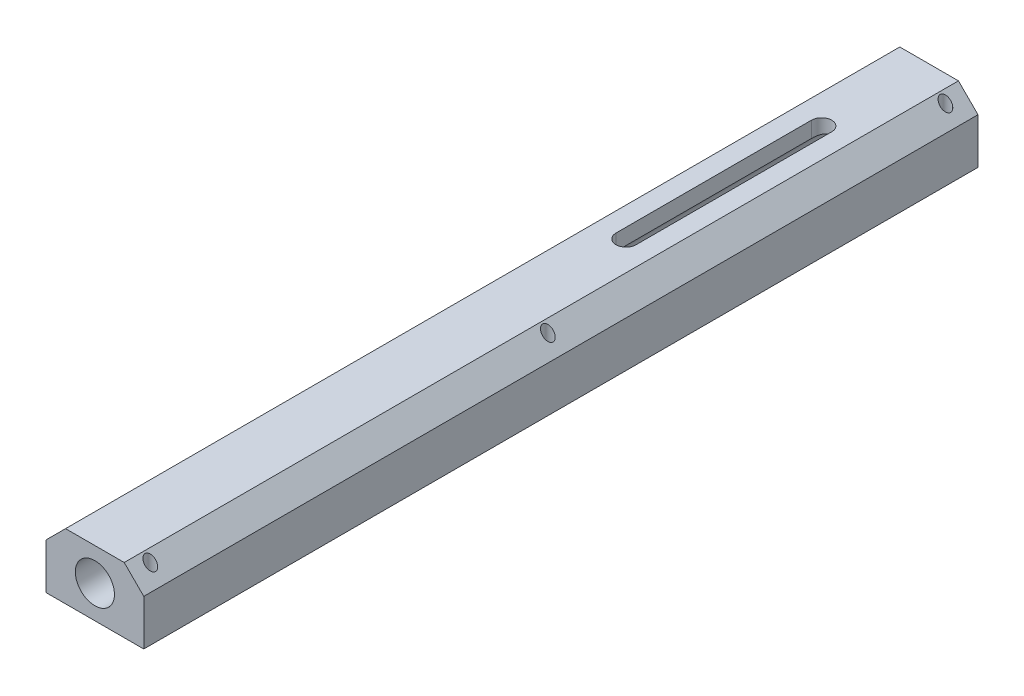
SolidWorks part; units mm, degrees
material "1.7014 (17CrS3)"
ref_plane "Plan de face" through (0, 0, 0) normal (0, 0, 1) x (1, 0, 0)
ref_plane "Plan de dessus" through (0, 0, 0) normal (0, 1, 0) x (1, 0, 0)
ref_plane "Plan de droite" through (0, 0, 0) normal (1, 0, 0) x (0, 0, -1)
sketch "Esquisse1" plane through (0, 0, 0) normal (0, 0, 1) x (1, 0, 0)
  line L0 (0, 0) -> (-9.5432, 0) construction
  line L1 (-7.5, 5) -> (7.5, 5)
  line L2 (-7.5, 5) -> (-7.5, -5)
  line L3 (-7.5, -5) -> (7.5, -5)
  line L4 (7.5, 5) -> (7.5, -5)
  line L5 (0, 0) -> (0, 7.4932) construction
  circle A0 centre (0, 0) radius 9 construction
  dimension "D1" = 15
  dimension "D2" = 10
extrude "Boss.-Extru.1" add sketch "Esquisse1" along normal blind 128
sketch "Esquisse2" plane through (0, 0, 128) normal (0, 0, 1) x (1, 0, 0)
  circle A0 centre (0, 0) radius 3
  dimension "D1" = 6
extrude "Enlèv. mat.-Extru.1" cut sketch "Esquisse2" against normal through all
sketch "Esquisse3" plane through (0, 5, 0) normal (0, 1, 0) x (1, 0, 0)
  line L0 (0, -16.5) -> (0, -46.5) construction
  line L1 (1.55, -16.5) -> (1.55, -46.5)
  line L2 (-1.55, -16.5) -> (-1.55, -46.5)
  line L3 (7.5, 0) -> (-7.5, 0) construction
  arc A0 (1.55, -16.5) -> (-1.55, -16.5) centre (0, -16.5) ccw
  arc A1 (-1.55, -46.5) -> (1.55, -46.5) centre (0, -46.5) ccw
  point P3 (0, -31.5)
  dimension "D1" = 1.55
  dimension "D2" = 16.5
  dimension "D3" = 30
extrude "Enlèv. mat.-Extru.2" cut sketch "Esquisse3" against normal through all
chamfer "Chanfrein1" distance 3 angle 45 2 edges at (7.5, 5, 64) (-7.5, 5, 64)
hole_wizard "Trou pour taraudage pour trou taraudé M21" positions "Esquisse4" profile "Esquisse5" hole size "M2" standard "ISO" end condition through all
sketch "Esquisse4" plane through (0, -5, 0) normal (0, -1, 0) x (-1, 0, 0)
  line L0 (7.5, -128) -> (-7.5, -128) construction
  line L1 (7.5, -128) -> (7.5, 0) construction
  point P0 (5.5, -125)
  dimension "D1" = 3
  dimension "D2" = 2
sketch "Esquisse5" plane through (-5.5, -5, 125) normal (1, 0, 0) x (0, 0, -1)
  line L0 (0, 0) -> (0, 10)
  line L1 (0, 10) -> (0.8, 10)
  line L2 (0.8, 10) -> (0.8, 0)
  line L5 (0.8, 0) -> (0, 0)
  line L11 (0, -6.35) -> (0, 107.95) construction
  dimension "Diamètre du perçage jusqu'au prochain" = 1.6
  dimension "Profondeur du perçage jusqu'au prochain" = 10
pattern_linear "Répétition linéaire1" count 3 spacing 61 along (0, 0, -1) count 2 spacing 11 along (1, 0, 0) of "Trou pour taraudage pour trou taraudé M21"
